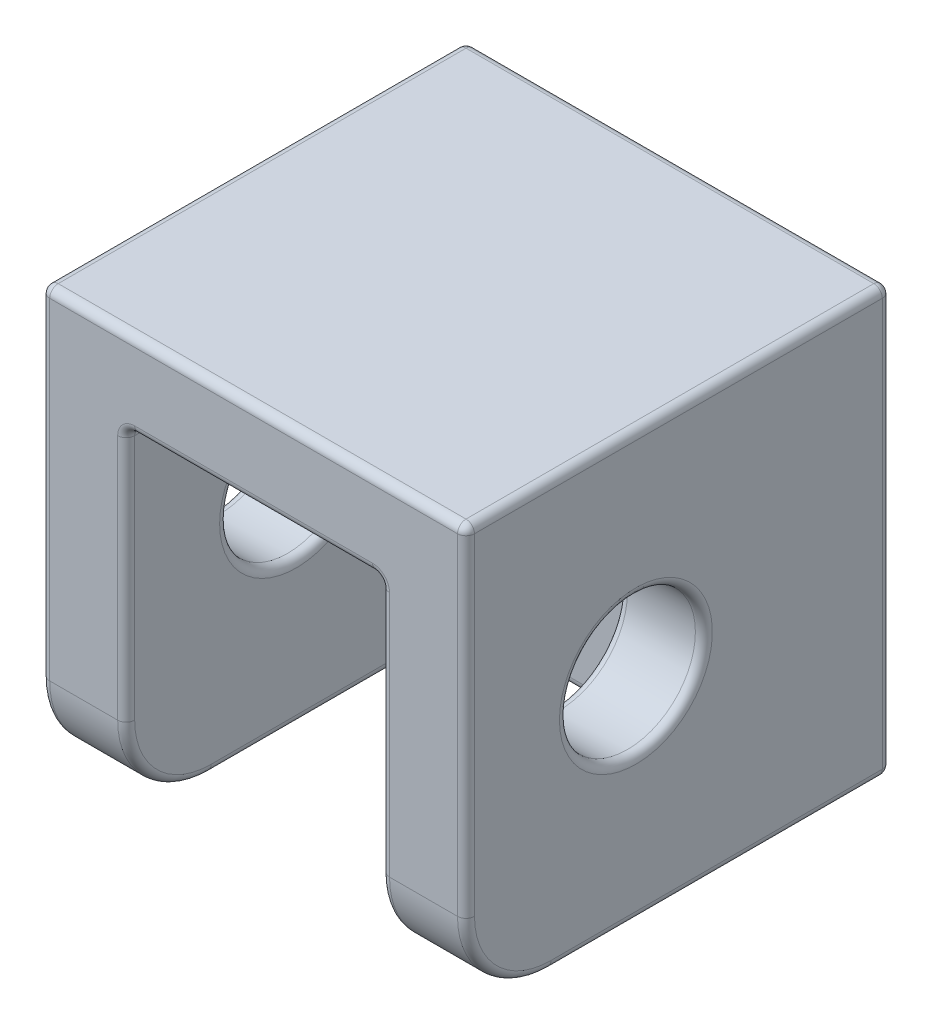
SolidWorks part; units mm, degrees
ref_plane "Front Plane" through (0, 0, 0) normal (0, 0, 1) x (1, 0, 0)
ref_plane "Top Plane" through (0, 0, 0) normal (0, 1, 0) x (1, 0, 0)
ref_plane "Right Plane" through (0, 0, 0) normal (1, 0, 0) x (0, 0, -1)
sketch "Sketch1" plane through (0, 0, 0) normal (0, 0, 1) x (1, 0, 0)
  line L1 (-25, -25) -> (25, -25)
  line L2 (-25, -25) -> (-25, 25)
  line L3 (-25, 25) -> (25, 25)
  line L4 (25, -25) -> (25, 25)
  line L5 (-25, -25) -> (25, 25) construction
  line L6 (-25, 25) -> (25, -25) construction
  point P0 (0, 0)
  dimension "D1" = 50
  dimension "D2" = 50
extrude "Boss-Extrude1" add sketch "Sketch1" along normal blind 50
sketch "Sketch2" plane through (0, 0, 50) normal (0, 0, 1) x (1, 0, 0)
  line L0 (-25, -25) -> (25, -25) construction
  line L1 (-15, -25) -> (15, -25)
  line L2 (-15, -25) -> (-15, 15)
  line L3 (-15, 15) -> (15, 15)
  line L4 (15, -25) -> (15, 15)
  line L5 (-25, 25) -> (-25, -25) construction
  point P0 (0, 0)
  dimension "D1" = 30
  dimension "D2" = 40
  dimension "D3" = 10
extrude "Cut-Extrude1" cut sketch "Sketch2" against normal blind 40
sketch "Sketch3" plane through (25, 0, 0) normal (1, 0, 0) x (0, 0, -1)
  line L0 (-50, -25) -> (-50, 25) construction
  circle A0 centre (-30, 0) radius 8
  dimension "D1" = 16
  dimension "D2" = 20
extrude "Cut-Extrude3" cut sketch "Sketch3" against normal blind 90
sketch "Sketch4" plane through (0, 0, 0) normal (0, 0, -1) x (-1, 0, 0)
  circle A0 centre (0, 0) radius 10.5
  dimension "D1" = 21
extrude "Cut-Extrude5" cut sketch "Sketch4" against normal blind 90
fillet "Fillet2" radius 10 2 edges at (20, -25, 50) (-20, -25, 50)
fillet "Fillet3" radius 1 26 edges at (-15, -22.0711, 47.0711) (-25, -22.0711, 47.0711) (25, -22.0711, 47.0711) (15, -22.0711, 47.0711) (0, -25, 0) (-25, -25, 20) (-15, -25, 25) (0, -25, 10) (15, -25, 25) (25, -25, 20) (15, 15, 30) (0, 15, 10) (-15, 15, 30) (25, 25, 25) (-25, 25, 25) (0, 25, 0) (0, 15, 50) (-15, 0, 50) (-25, 5, 50) (0, 25, 50) (25, 5, 50) (15, 0, 50) (-15, -5, 10) (15, -5, 10) (25, 0, 0) (-25, 0, 0)
fillet "Fillet4" radius 1 4 edges at (15, 0, 22) (-15, 0, 38) (-25, 0, 22) (25, 0, 22)
